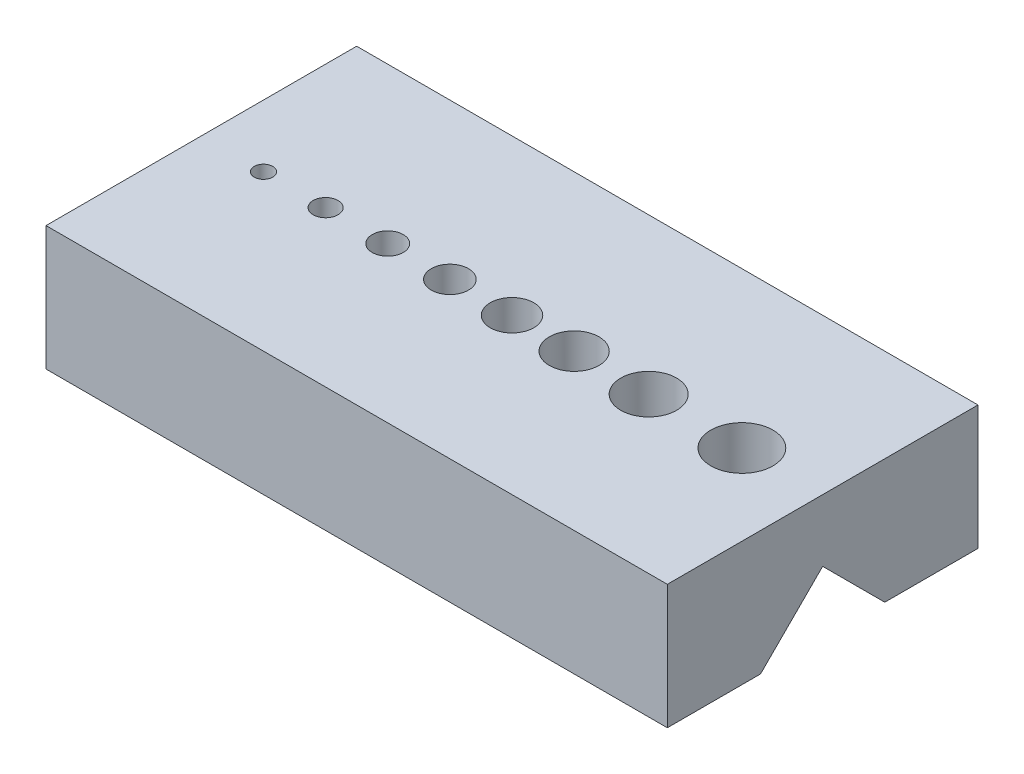
SolidWorks part; units mm, degrees
ref_plane "Front Plane" through (0, 0, 0) normal (0, 0, 1) x (1, 0, 0)
ref_plane "Top Plane" through (0, 0, 0) normal (0, 1, 0) x (1, 0, 0)
ref_plane "Right Plane" through (0, 0, 0) normal (1, 0, 0) x (0, 0, -1)
sketch "Sketch1" plane through (0, 0, 0) normal (0, 1, 0) x (1, 0, 0)
  line L1 (0, 0) -> (100, 0)
  line L2 (0, 0) -> (0, 50)
  line L3 (0, 50) -> (100, 50)
  line L4 (100, 0) -> (100, 50)
  circle A0 centre (10, 25) radius 1.5
  circle A1 centre (20, 25) radius 2
  circle A2 centre (30, 25) radius 2.5
  circle A3 centre (40, 25) radius 3
  circle A10 centre (50, 25) radius 3.5
  circle A11 centre (60, 25) radius 4
  circle A12 centre (72, 25) radius 4.5
  circle A13 centre (87, 25) radius 5
  point P21 (0, 0)
  dimension "D3" = 3
  dimension "D4" = 4
  dimension "D5" = 5
  dimension "D6" = 6
  dimension "D2" = 7
  dimension "D12" = 8
  dimension "D13" = 9
  dimension "D14" = 10
  dimension "D1" = 50
  dimension "50" = 100
  dimension "D7" = 10
  dimension "D8" = 10
  dimension "D9" = 10
  dimension "D10" = 10
  dimension "D11" = 25
  dimension "D15" = 15
  dimension "D16" = 10
  dimension "D17" = 10
  dimension "D18" = 12
extrude "Boss-Extrude1" add sketch "Sketch1" along normal blind 20
sketch "Sketch2" plane through (100, 0, 0) normal (1, 0, 0) x (0, 0, -1)
  line L0 (15, 0) -> (25, 10)
  line L2 (25, 10) -> (35, 0)
  line L4 (0, 0) -> (50, 0) construction
  line L5 (25, 10) -> (25, 0) construction
  line L6 (15, 0) -> (35, 0)
  point P1 (25, 0)
  dimension "D1" = 25
  dimension "D4" = 10
extrude "Cut-Extrude2" cut sketch "Sketch2" against normal through all
